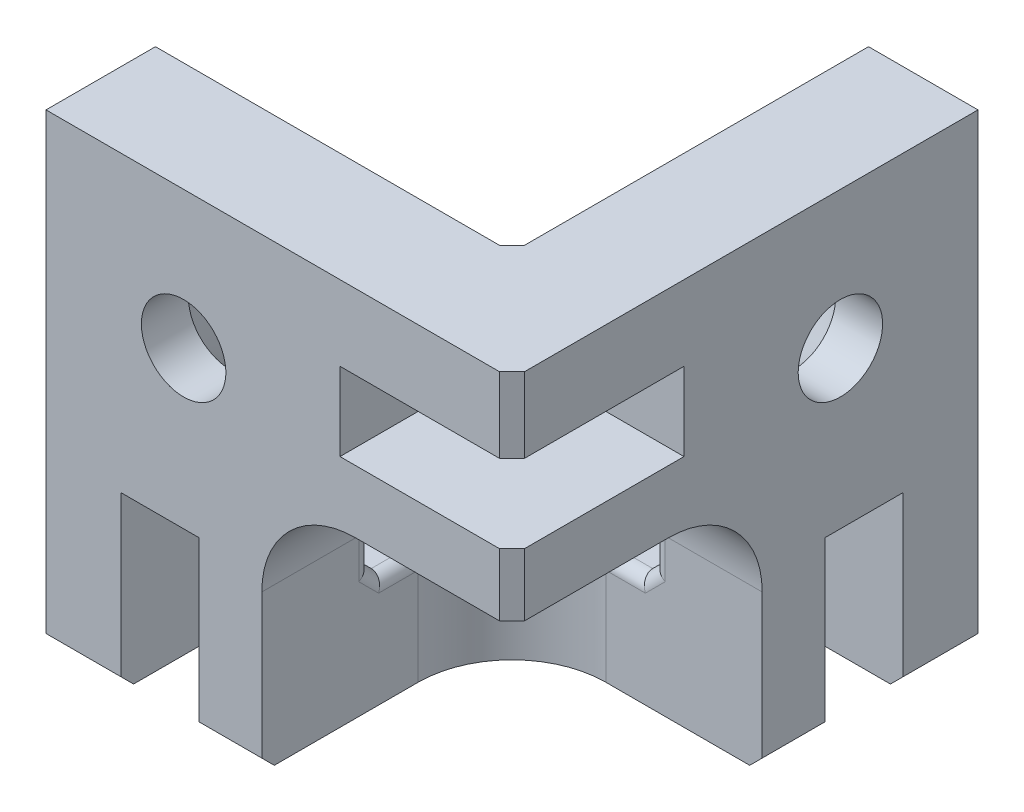
SolidWorks part; units mm, degrees
ref_plane "Plan de face" through (0, 0, 0) normal (0, 0, 1) x (1, 0, 0)
ref_plane "Plan de dessus" through (0, 0, 0) normal (0, 1, 0) x (1, 0, 0)
ref_plane "Plan de droite" through (0, 0, 0) normal (1, 0, 0) x (0, 0, -1)
sketch "Esquisse1" plane through (0, 0, 0) normal (0, 1, 0) x (1, 0, 0)
  line L13 (-8, 8) -> (8, 8)
  line L14 (-8, 8) -> (-8, -8)
  line L15 (-8, -8) -> (8, -8)
  line L16 (8, 8) -> (8, -8)
  line L17 (-8, 8) -> (8, -8) construction
  line L18 (-8, -8) -> (8, 8) construction
  point P0 (0, 0)
  dimension "D1" = 16
extrude "Boss.-Extru.1" add sketch "Esquisse1" along normal blind 16
shell "Coque2" thickness 3.5
sketch "Esquisse2" plane through (0, 0, 0) normal (0, -1, 0) x (1, 0, 0)
  line L0 (-8, 8) -> (8, 8) construction
  line L1 (-4.5, 8) -> (-2, 8)
  line L2 (-4.5, 8) -> (-4.5, 2.5)
  line L3 (-4.5, 2.5) -> (-2, 2.5)
  line L4 (-2, 8) -> (-2, 2.5)
  line L5 (8, 8) -> (8, -8) construction
  line L6 (8, -2) -> (2.5, -2)
  line L7 (8, -2) -> (8, -4.5)
  line L8 (8, -4.5) -> (2.5, -4.5)
  line L9 (2.5, -2) -> (2.5, -4.5)
  dimension "D1" = 5.5
  dimension "D2" = 2.5
  dimension "D3" = 10
  dimension "D4" = 10
extrude "Enlèv. mat.-Extru.1" cut sketch "Esquisse2" against normal blind 5.5
sketch "Esquisse3" plane through (0, 0, 8) normal (0, 0, 1) x (1, 0, 0)
  line L0 (8, 16) -> (8, 0) construction
  line L1 (8, 12.5) -> (2.5, 12.5)
  line L2 (8, 12.5) -> (8, 10)
  line L3 (8, 10) -> (2.5, 10)
  line L4 (2.5, 12.5) -> (2.5, 10)
  dimension "D1" = 5.5
  dimension "D2" = 2.5
  dimension "D3" = 10
extrude "Enlèv. mat.-Extru.2" cut sketch "Esquisse3" against normal blind 5.5
sketch "Esquisse7" plane through (0, 0, 0) normal (0, -1, 0) x (1, 0, 0)
  line L0 (-2, 8) -> (8, 8) construction
  line L1 (8, 8) -> (8, -2) construction
  line L2 (3, 0) -> (8, 0)
  line L3 (8, 0) -> (8, 8)
  line L4 (8, 8) -> (0, 8)
  line L5 (0, 8) -> (0, 3)
  arc A0 (0, 3) -> (3, 0) centre (3, 3) ccw
  dimension "D3" = 6
  dimension "D1" = 5
  dimension "D2" = 5
extrude "Enlèv. mat.-Extru.3" cut sketch "Esquisse7" against normal up to surface (3.5 mm away) up to face at (-0.5, 3.5, -0.5)
sketch "Esquisse8" plane through (0, 0, 8) normal (0, 0, 1) x (1, 0, 0)
  line L0 (-2, 0) -> (0, 0) construction
  line L1 (8, 10) -> (8, 3.5) construction
  line L2 (3, 8) -> (8, 8)
  line L3 (8, 8) -> (8, 0)
  line L4 (8, 0) -> (0, 0)
  line L5 (0, 0) -> (0, 5)
  arc A0 (3, 8) -> (0, 5) centre (3, 5) ccw
  dimension "D3" = 6
  dimension "D1" = 5
  dimension "D2" = 5
extrude "Enlèv. mat.-Extru.4" cut sketch "Esquisse8" against normal up to surface (3.5 mm away) up to face at (-0.4615, 8.1154, 4.5)
sketch "Esquisse9" plane through (8, 0, 0) normal (1, 0, 0) x (0, 0, -1)
  line L0 (-8, 10) -> (-8, 8) construction
  line L1 (0, 0) -> (2, 0) construction
  line L2 (-3, 8) -> (-8, 8)
  line L3 (-8, 8) -> (-8, 0)
  line L4 (-8, 0) -> (0, 0)
  line L5 (0, 0) -> (0, 5)
  arc A0 (0, 5) -> (-3, 8) centre (-3, 5) ccw
  dimension "D3" = 6
  dimension "D1" = 5
  dimension "D2" = 5
extrude "Enlèv. mat.-Extru.5" cut sketch "Esquisse9" against normal up to surface (3.5 mm away) up to face at (4.5, 8.1071, -0.1071)
hole_wizard "Fraisage pour vis à tête fraisée M2.51" positions "Esquisse3D1" profile "Esquisse17" countersink size "M2.5" standard "ISO" end condition through all
sketch3d "Esquisse3D1"
  line L0 (4.5, 16, 4.5) -> (4.5, 16, -8) construction
  line L1 (4.5, 16, -8) -> (4.5, 3.5, -8) construction
  line L2 (-8, 3.5, -8) -> (-8, 3.5, 4.5) construction
  line L3 (4.5, 3.5, -8) -> (-8, 3.5, -8) construction
  line L4 (-8, 16, 4.5) -> (4.5, 16, 4.5) construction
  line L5 (-8, 16, 4.5) -> (-8, 3.5, 4.5) construction
  point P0 (4.5, 10.5, -2.5)
  point P2 (-2.5, 10.5, 4.5)
  point P4 (-2.5, 3.5, -2.5)
  dimension "D1" = 5.5
  dimension "D2" = 5.5
  dimension "D3" = 5.5
  dimension "D4" = 5.5
  dimension "D5" = 5.5
  dimension "D6" = 5.5
sketch "Esquisse17" plane through (4.5, 10.5, -2.5) normal (0, 1, 0) x (0, 0, 1)
  line L0 (0, 0) -> (0, 3.5)
  line L1 (0, 3.5) -> (1.35, 3.5)
  line L2 (1.35, 3.5) -> (1.35, 2)
  line L3 (1.35, 2) -> (3.35, 0)
  line L5 (3.35, 0) -> (0, 0)
  line L6 (-1.35, 2) -> (-3.35, 0) construction
  line L11 (0, -6.35) -> (0, 107.95) construction
  dimension "Diamètre du perçage jusqu'au prochain" = 2.7
  dimension "Profondeur du perçage jusqu'au prochain" = 3.5
  dimension "Diamètre du fraisage entrant" = 6.7
  dimension "Angle du fraisage entrant" = 90
sketch "Esquisse10" plane through (0, 16, 0) normal (0, 1, 0) x (1, 0, 0)
  line L0 (4.5, 8) -> (4.5, -4.5)
  line L1 (4.5, -4.5) -> (-8, -4.5)
  line L2 (-8, -4.5) -> (-8, -8)
  line L3 (-8, -8) -> (8, -8)
  line L4 (8, -8) -> (8, 8)
  line L5 (8, 8) -> (4.5, 8)
extrude "Enlèv. mat.-Extru.6" cut sketch "Esquisse10" against normal blind 1.1
sketch "Esquisse11" plane through (0, 0, -8) normal (0, 0, -1) x (-1, 0, 0)
  line L12 (-4.5, 14.9) -> (-8, 14.9)
  line L13 (-8, 14.9) -> (-8, 0)
  line L14 (-8, 0) -> (8, 0)
  line L15 (8, 0) -> (8, 3.5)
  line L16 (8, 3.5) -> (-4.5, 3.5)
  line L17 (-4.5, 3.5) -> (-4.5, 14.9)
  line L18 (-4.5, 14.9) -> (-8, 14.9)
  line L19 (-8, 14.9) -> (-8, 0)
  line L20 (-8, 0) -> (8, 0)
  line L21 (8, 0) -> (8, 3.5)
  line L22 (8, 3.5) -> (-4.5, 3.5)
  line L23 (-4.5, 3.5) -> (-4.5, 14.9)
  dimension "D1" = 0
extrude "Enlèv. mat.-Extru.7" cut sketch "Esquisse11" against normal blind 1.1
sketch "Esquisse13" plane through (-8, 0, 0) normal (-1, 0, 0) x (0, 0, 1)
  line L12 (-6.9, 3.5) -> (-6.9, 0)
  line L13 (-6.9, 0) -> (8, 0)
  line L14 (8, 0) -> (8, 14.9)
  line L15 (8, 14.9) -> (4.5, 14.9)
  line L16 (4.5, 14.9) -> (4.5, 3.5)
  line L17 (4.5, 3.5) -> (-6.9, 3.5)
  line L18 (-6.9, 3.5) -> (-6.9, 0)
  line L19 (-6.9, 0) -> (8, 0)
  line L20 (8, 0) -> (8, 14.9)
  line L21 (8, 14.9) -> (4.5, 14.9)
  line L22 (4.5, 14.9) -> (4.5, 3.5)
  line L23 (4.5, 3.5) -> (-6.9, 3.5)
  dimension "D1" = 0
extrude "Enlèv. mat.-Extru.8" cut sketch "Esquisse13" against normal blind 1.1
chamfer "Chanfrein1" distance 0.4 angle 45 12 edges at (4.5, 13.7, 4.5) (-5.7, 3.5, 4.5) (4.5, 9, 4.5) (-1, 3.5, 4.5) (4.5, 3.5, -1) (4.5, 3.5, -5.7) (8, 0, -5.7) (-5.7, 0, 8) (8, 13.7, 8) (8, 0, -1) (8, 9, 8) (-1, 0, 8)
fillet "Congé1" radius 0.4 12 edges at (0.8787, 3.5, 0.8787) (0.8787, 7.1213, 4.5) (4.5, 7.1213, 0.8787) (4.5, 4.45, 0) (4.5, 8, 3.55) (3.55, 8, 4.5) (0, 4.45, 4.5) (0, 3.5, 3.55) (3.55, 3.5, 0) (4.3, 8, 4.3) (0, 3.7, 4.3) (4.3, 3.7, 0)
